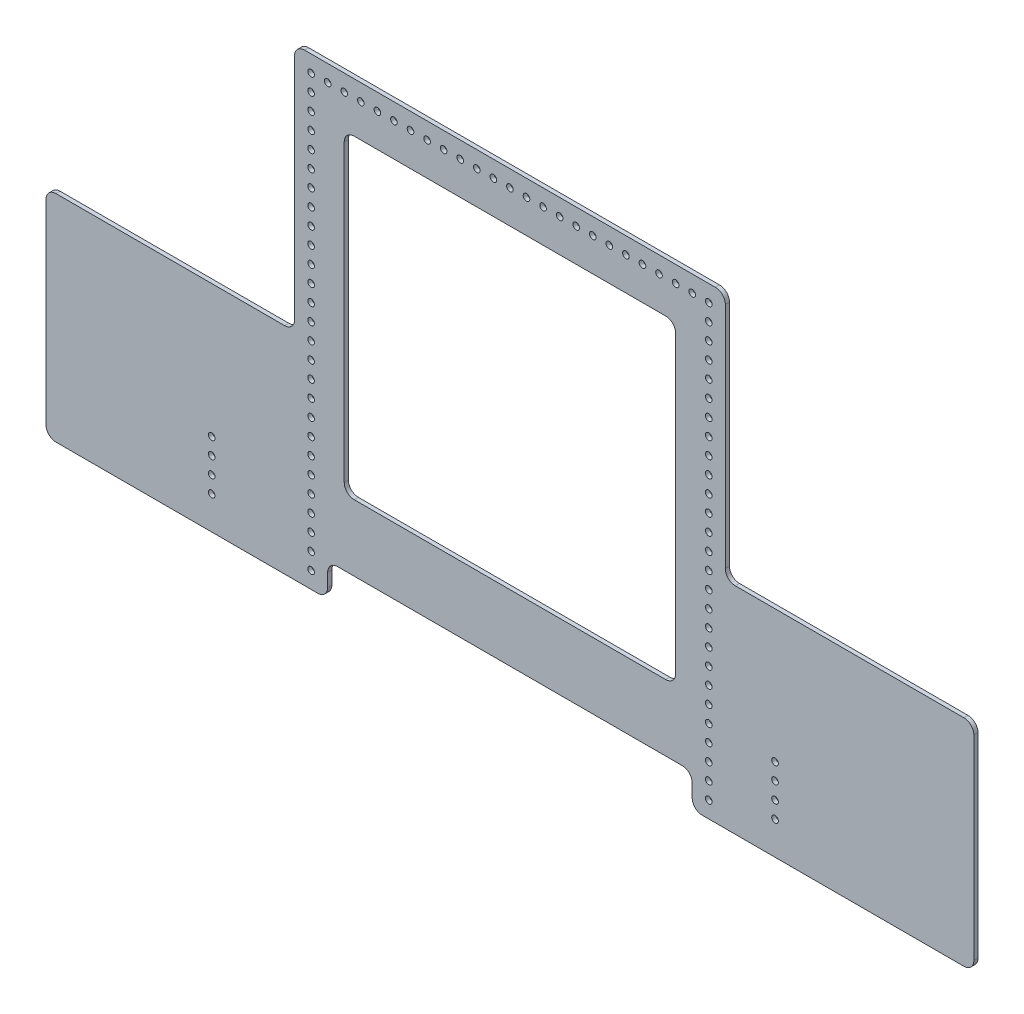
SolidWorks part; units mm, degrees
ref_plane "Front Plane" through (0, 0, 0) normal (0, 0, 1) x (1, 0, 0)
ref_plane "Top Plane" through (0, 0, 0) normal (0, 1, 0) x (1, 0, 0)
ref_plane "Right Plane" through (0, 0, 0) normal (1, 0, 0) x (0, 0, -1)
sketch "Sketch1" plane through (0, 0, 0) normal (0, 0, 1) x (1, 0, 0)
  line L0 (392.0157, -380.5307) -> (607.9157, -380.5307)
  line L1 (87.2157, -25.0533) -> (417.4157, -25.0533)
  line L2 (-103.2843, -215.5533) -> (-103.2843, -380.5307)
  line L3 (-103.2843, -380.5307) -> (112.6157, -380.5307)
  line L4 (607.9157, -215.5533) -> (607.9157, -380.5307)
  line L7 (-103.2843, -215.5533) -> (87.2157, -215.5533)
  line L8 (87.2157, -25.0533) -> (87.2157, -215.5533)
  line L11 (607.9157, -215.5533) -> (417.4157, -215.5533)
  line L12 (417.4157, -25.0533) -> (417.4157, -215.5533)
  line L14 (112.6157, -380.5307) -> (112.6157, -355.2533)
  line L15 (112.6157, -355.2533) -> (392.0157, -355.2533)
  line L16 (392.0157, -380.5307) -> (392.0157, -355.2533)
  line L17 (125.3157, -63.1533) -> (379.3157, -63.1533)
  line L18 (125.3157, -63.1533) -> (125.3157, -304.4533)
  line L19 (125.3157, -304.4533) -> (379.3157, -304.4533)
  line L20 (379.3157, -63.1533) -> (379.3157, -304.4533)
  circle A0 centre (99.9157, -37.7533) radius 2.54
  circle A1 centre (112.6157, -37.7533) radius 2.54
  circle A2 centre (125.3157, -37.7533) radius 2.54
  circle A3 centre (138.0157, -37.7533) radius 2.54
  circle A4 centre (150.7157, -37.7533) radius 2.54
  circle A5 centre (163.4157, -37.7533) radius 2.54
  circle A6 centre (176.1157, -37.7533) radius 2.54
  circle A7 centre (188.8157, -37.7533) radius 2.54
  circle A8 centre (201.5157, -37.7533) radius 2.54
  circle A9 centre (214.2157, -37.7533) radius 2.54
  circle A10 centre (226.9157, -37.7533) radius 2.54
  circle A11 centre (239.6157, -37.7533) radius 2.54
  circle A12 centre (252.3157, -37.7533) radius 2.54
  circle A13 centre (265.0157, -37.7533) radius 2.54
  circle A14 centre (277.7157, -37.7533) radius 2.54
  circle A15 centre (290.4157, -37.7533) radius 2.54
  circle A16 centre (303.1157, -37.7533) radius 2.54
  circle A17 centre (315.8157, -37.7533) radius 2.54
  circle A18 centre (328.5157, -37.7533) radius 2.54
  circle A19 centre (341.2157, -37.7533) radius 2.54
  circle A20 centre (353.9157, -37.7533) radius 2.54
  circle A21 centre (366.6157, -37.7533) radius 2.54
  circle A22 centre (379.3157, -37.7533) radius 2.54
  circle A23 centre (392.0157, -37.7533) radius 2.54
  circle A24 centre (404.7157, -37.7533) radius 2.54
  circle A25 centre (99.9157, -50.4533) radius 2.54
  circle A26 centre (99.9157, -63.1533) radius 2.54
  circle A27 centre (99.9157, -75.8533) radius 2.54
  circle A28 centre (99.9157, -88.5533) radius 2.54
  circle A29 centre (99.9157, -101.2533) radius 2.54
  circle A30 centre (99.9157, -113.9533) radius 2.54
  circle A31 centre (99.9157, -126.6533) radius 2.54
  circle A32 centre (99.9157, -139.3533) radius 2.54
  circle A33 centre (99.9157, -152.0533) radius 2.54
  circle A34 centre (99.9157, -164.7533) radius 2.54
  circle A35 centre (99.9157, -177.4533) radius 2.54
  circle A36 centre (99.9157, -190.1533) radius 2.54
  circle A37 centre (99.9157, -202.8533) radius 2.54
  circle A38 centre (99.9157, -215.5533) radius 2.54
  circle A39 centre (99.9157, -228.2533) radius 2.54
  circle A40 centre (99.9157, -240.9533) radius 2.54
  circle A41 centre (99.9157, -253.6533) radius 2.54
  circle A42 centre (99.9157, -266.3533) radius 2.54
  circle A43 centre (99.9157, -279.0533) radius 2.54
  circle A44 centre (99.9157, -291.7533) radius 2.54
  circle A45 centre (99.9157, -304.4533) radius 2.54
  circle A46 centre (99.9157, -317.1533) radius 2.54
  circle A47 centre (99.9157, -329.8533) radius 2.54
  circle A48 centre (99.9157, -342.5533) radius 2.54
  circle A49 centre (99.9157, -355.2533) radius 2.54
  circle A50 centre (99.9157, -367.9533) radius 2.54
  circle A51 centre (404.7157, -50.4533) radius 2.54
  circle A52 centre (404.7157, -63.1533) radius 2.54
  circle A53 centre (404.7157, -75.8533) radius 2.54
  circle A54 centre (404.7157, -88.5533) radius 2.54
  circle A55 centre (404.7157, -101.2533) radius 2.54
  circle A56 centre (404.7157, -113.9533) radius 2.54
  circle A57 centre (404.7157, -126.6533) radius 2.54
  circle A58 centre (404.7157, -139.3533) radius 2.54
  circle A59 centre (404.7157, -152.0533) radius 2.54
  circle A60 centre (404.7157, -164.7533) radius 2.54
  circle A61 centre (404.7157, -177.4533) radius 2.54
  circle A62 centre (404.7157, -190.1533) radius 2.54
  circle A63 centre (404.7157, -202.8533) radius 2.54
  circle A64 centre (404.7157, -215.5533) radius 2.54
  circle A65 centre (404.7157, -228.2533) radius 2.54
  circle A66 centre (404.7157, -240.9533) radius 2.54
  circle A67 centre (404.7157, -253.6533) radius 2.54
  circle A68 centre (404.7157, -266.3533) radius 2.54
  circle A69 centre (404.7157, -279.0533) radius 2.54
  circle A70 centre (404.7157, -291.7533) radius 2.54
  circle A71 centre (404.7157, -304.4533) radius 2.54
  circle A72 centre (404.7157, -317.1533) radius 2.54
  circle A73 centre (404.7157, -329.8533) radius 2.54
  circle A74 centre (404.7157, -342.5533) radius 2.54
  circle A75 centre (404.7157, -355.2533) radius 2.54
  circle A76 centre (404.7157, -367.9533) radius 2.54
  circle A77 centre (23.7157, -317.1533) radius 2.54
  circle A78 centre (455.5157, -317.1533) radius 2.54
  circle A79 centre (455.5157, -329.8533) radius 2.54
  circle A80 centre (455.5157, -342.5533) radius 2.54
  circle A81 centre (455.5157, -355.2533) radius 2.54
  circle A82 centre (23.7157, -329.8533) radius 2.54
  circle A83 centre (23.7157, -342.5533) radius 2.54
  circle A84 centre (23.7157, -355.2533) radius 2.54
  dimension "D13" = 12.7
  dimension "D5" = 101.6
  dimension "D1" = 190.5
  dimension "D2" = 190.5
  dimension "D3" = 190.5
  dimension "D4" = 190.5
  dimension "D6" = 50.8
  dimension "D7" = 330.2
  dimension "D8" = 279.4
  dimension "D9" = 215.9
  dimension "D10" = 38.1
  dimension "D11" = 38.1
  dimension "D12" = 38.1
  dimension "D14" = 12.7
  dimension "6" = 127
  dimension "D15" = 25
  dimension "D16" = 27
  dimension "D17" = 27
  dimension "D18" = 4
extrude "Boss-Extrude1" add sketch "Sketch1" along normal blind 3.175
fillet "Fillet1" radius 7.62 16 edges at (125.3157, -63.1533, 1.5875) (379.3157, -304.4533, 1.5875) (379.3157, -63.1533, 1.5875) (-103.2843, -380.5307, 1.5875) (112.6157, -380.5307, 1.5875) (392.0157, -380.5307, 1.5875) (392.0157, -355.2533, 1.5875) (112.6157, -355.2533, 1.5875) (607.9157, -380.5307, 1.5875) (607.9157, -215.5533, 1.5875) (417.4157, -215.5533, 1.5875) (417.4157, -25.0533, 1.5875) (87.2157, -25.0533, 1.5875) (-103.2843, -215.5533, 1.5875) (87.2157, -215.5533, 1.5875) (125.3157, -304.4533, 1.5875)
